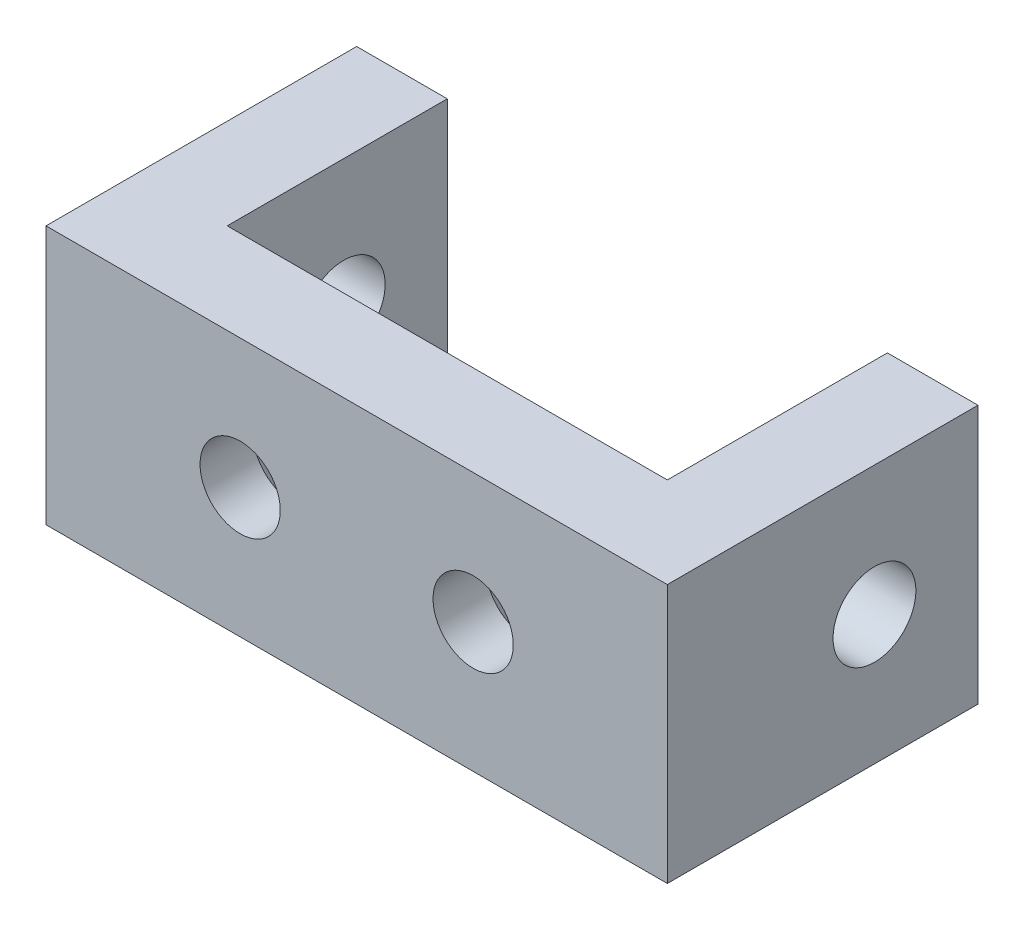
SolidWorks part; units mm, degrees
ref_plane "Front" through (0, 0, 0) normal (0, 0, 1) x (1, 0, 0)
ref_plane "Top" through (0, 0, 0) normal (0, 1, 0) x (1, 0, 0)
ref_plane "Right" through (0, 0, 0) normal (1, 0, 0) x (0, 0, -1)
sketch "Sketch1" plane through (0, 0, 0) normal (0, 1, 0) x (1, 0, 0)
  line L1 (-8.5, -1.75) -> (8.5, -1.75)
  line L2 (-8.5, -1.75) -> (-8.5, 1.75)
  line L3 (-8.5, 1.75) -> (8.5, 1.75)
  line L4 (8.5, -1.75) -> (8.5, 1.75)
  line L5 (-8.5, -1.75) -> (8.5, 1.75) construction
  line L6 (-8.5, 1.75) -> (8.5, -1.75) construction
  line L7 (8.5, -1.75) -> (12, -1.75)
  line L8 (8.5, -1.75) -> (8.5, 10.25)
  line L9 (8.5, 10.25) -> (12, 10.25)
  line L10 (12, -1.75) -> (12, 10.25)
  line L11 (8.5, -1.75) -> (12, 10.25) construction
  line L12 (8.5, 10.25) -> (12, -1.75) construction
  line L13 (-8.5, -1.75) -> (-12, -1.75)
  line L14 (-8.5, -1.75) -> (-8.5, 10.25)
  line L15 (-8.5, 10.25) -> (-12, 10.25)
  line L16 (-12, -1.75) -> (-12, 10.25)
  line L17 (-8.5, -1.75) -> (-12, 10.25) construction
  line L18 (-8.5, 10.25) -> (-12, -1.75) construction
  point P0 (0, 0)
  point P9 (10.25, 4.25)
  point P13 (-10.25, 4.25)
  dimension "D1" = 3.5
  dimension "D2" = 17
  dimension "D3" = 12
  dimension "D4" = 3.5
  dimension "D5" = 12
  dimension "D6" = 3.5
extrude "Boss-Extrude1" add sketch "Sketch1" along normal blind 10 contours L16 L13 L2 L14 L15 | L1 L4 L3 L2 | L7 L10 L9 L8 L4
sketch "Sketch2" plane through (-12, 0, 0) normal (-1, 0, 0) x (0, 0, 1)
  line L0 (-10.25, 5) -> (-6.25, 5) construction
  line L1 (-10.25, 10) -> (-10.25, 0) construction
  circle A0 centre (-6.25, 5) radius 1.6
  dimension "D2" = 3.2
  dimension "D1" = 4
extrude "Cut-Extrude1" cut sketch "Sketch2" against normal through all
sketch "Sketch3" plane through (0, 0, -1.75) normal (0, 0, -1) x (-1, 0, 0)
  line L0 (8.5, 0) -> (-8.5, 0) construction
  circle A0 centre (-4.5, 5) radius 1.5
  circle A1 centre (4.5, 5) radius 1.5
  point P7 (0, 0)
  dimension "D1" = 3
  dimension "D2" = 3
  dimension "D3" = 5
  dimension "D4" = 4.5
  dimension "D5" = 4.5
extrude "Cut-Extrude2" cut sketch "Sketch3" against normal through all
hole_wizard "CSK for M4 Countersunk Flat Head Screw1" positions "3DSketch1" profile "Sketch4" countersink size "M4" standard "ISO" end condition through all
sketch3d "3DSketch1"
  line L0 (4.5, 5, 1.75) -> (4.5, 5, -1.75) construction
  line L1 (-4.5, 5, 1.75) -> (-4.5, 5, -1.75) construction
  point P0 (4.5, 5, -1.75)
  point P4 (-4.5, 5, -1.75)
sketch "Sketch4" plane through (4.5, 5, -1.75) normal (1, 0, 0) x (0, 1, 0)
  line L0 (0, 0) -> (0, 3.5)
  line L1 (0, 3.5) -> (1.55, 3.5)
  line L2 (1.55, 3.5) -> (1.55, 1.45)
  line L3 (1.55, 1.45) -> (3, 0)
  line L5 (3, 0) -> (0, 0)
  line L6 (-1.55, 1.45) -> (-3, 0) construction
  line L11 (0, -6.35) -> (0, 107.95) construction
  dimension "Thru Hole Dia." = 3.1
  dimension "Thru Hole Depth" = 3.5
  dimension "Near C'Sink Dia." = 6
  dimension "Near C'Sink Angle" = 90
